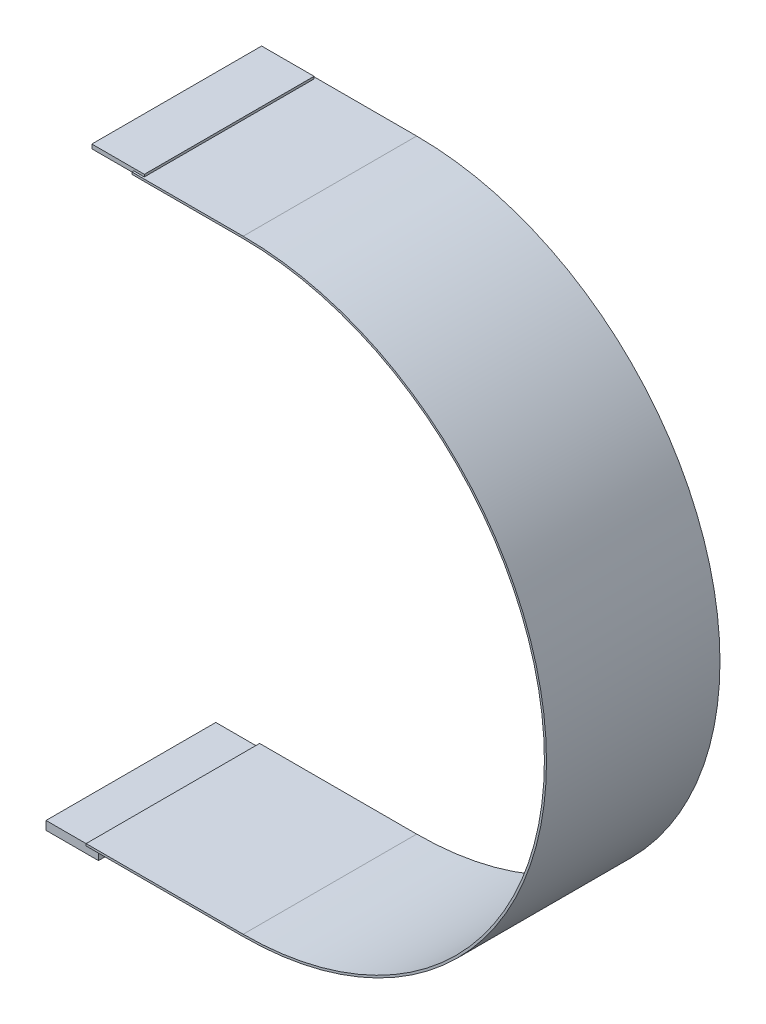
SolidWorks part; units mm, degrees
ref_plane "Front Plane" through (0, 0, 0) normal (0, 0, 1) x (1, 0, 0)
ref_plane "Top Plane" through (0, 0, 0) normal (0, 1, 0) x (1, 0, 0)
ref_plane "Right Plane" through (0, 0, 0) normal (1, 0, 0) x (0, 0, -1)
sketch "Sketch1" plane through (0, 0, 0) normal (0, 0, 1) x (1, 0, 0)
  line L0 (0, 0) -> (19.0118, 0)
  line L1 (19.0118, 73.4298) -> (5.549, 73.4298)
  line L2 (5.549, 73.4298) -> (5.549, 73.1758)
  line L3 (0, 0.254) -> (19.0118, 0.254)
  line L4 (19.0118, 73.1758) -> (5.549, 73.1758)
  line L5 (0, 0.254) -> (0, 0)
  arc A0 (19.0118, 0) -> (19.0118, 73.4298) centre (19.0118, 36.7149) ccw
  arc A1 (19.0118, 0.254) -> (19.0118, 73.1758) centre (19.0118, 36.7149) ccw
  dimension "D1" = 0.254
  dimension "D2" = 13.4628
  dimension "D3" = 19.0118
  dimension "D4" = 73.1758
extrude "Boss-Extrude1" add sketch "Sketch1" along normal mid plane 21
sketch "Sketch2" plane through (0, 73.4298, 0) normal (0, 1, 0) x (1, 0, 0)
  line L1 (0.9141, -9.0735) -> (55.7266, -9.0735)
  line L2 (0.9141, -9.0735) -> (0.9141, -8.8195)
  line L3 (0.9141, -8.8195) -> (55.7266, -8.8195)
  line L4 (55.7266, -9.0735) -> (55.7266, -8.8195)
  line L5 (55.7266, -10.5) -> (55.7266, 10.5) construction
  dimension "D1" = 0.254
extrude "Cut-Extrude1" [suppressed] cut sketch "Sketch2" against normal through all
sketch "Sketch3" plane through (0, 0, 0) normal (-1, 0, 0) x (0, 0, 1)
  line L0 (10.5, 0) -> (-10.5, 0) construction
  line L1 (-10.2743, 0.0254) -> (10.2743, 0.0254)
  line L2 (-10.2743, 0.0254) -> (-10.2743, -1.016)
  line L3 (-10.2743, -1.016) -> (10.2743, -1.016)
  line L4 (10.2743, 0.0254) -> (10.2743, -1.016)
  point P6 (0, -1.016)
  dimension "D1" = 1.0414
  dimension "D2" = 20.5486
  dimension "D3" = 0.0254
extrude "Boss-Extrude2" add sketch "Sketch3" along normal blind 5.08 and the other way blind 1.27
sketch "Sketch4" plane through (5.549, 0, 0) normal (-1, 0, 0) x (0, 0, 1)
  line L1 (-10.2743, 73.2012) -> (10.2743, 73.2012)
  line L2 (-10.2743, 73.2012) -> (-10.2743, 73.7092)
  line L3 (-10.2743, 73.7092) -> (10.2743, 73.7092)
  line L4 (10.2743, 73.2012) -> (10.2743, 73.7092)
  line L5 (10.5, 73.1758) -> (-10.5, 73.1758) construction
  point P6 (0, 73.7092)
  dimension "D1" = 0.508
  dimension "D2" = 20.5486
  dimension "D3" = 0.0254
extrude "Boss-Extrude3" add sketch "Sketch4" along normal blind 5.08 and the other way blind 1.27
